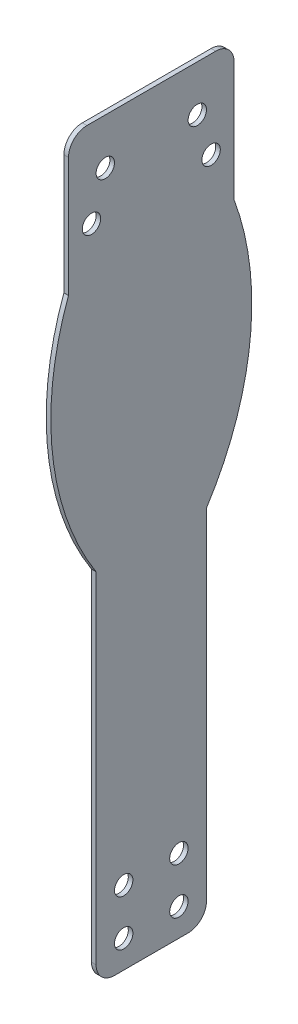
SolidWorks part; units mm, degrees
material "PVC 0.007 Plasticized"
ref_plane "Front Plane" through (0, 0, 0) normal (0, 0, 1) x (1, 0, 0)
ref_plane "Top Plane" through (0, 0, 0) normal (0, 1, 0) x (1, 0, 0)
ref_plane "Right Plane" through (0, 0, 0) normal (1, 0, 0) x (0, 0, -1)
sketch "Sketch1" plane through (0, 0, 0) normal (1, 0, 0) x (0, 0, -1)
  line L0 (12, -163) -> (12, -85)
  line L1 (-18, 0) -> (18, 0)
  line L2 (-18, 0) -> (-18, -163) construction
  line L3 (-18, -163) -> (18, -163) construction
  line L4 (18, 0) -> (18, -163) construction
  line L5 (-18, 0) -> (18, -163) construction
  line L6 (-18, -163) -> (18, 0) construction
  line L7 (-12, -163) -> (-12, -85)
  line L8 (12, -85) -> (-12, -85) construction
  line L9 (18, -30) -> (-18, -30) construction
  line L10 (18, 0) -> (18, -30)
  line L11 (-18, 0) -> (-18, -30)
  line L12 (-21.8408, -51.4826) -> (21.8408, -51.4826) construction
  line L13 (12, -163) -> (-12, -163)
  arc A0 (18, -30) -> (12, -85) centre (-40.1592, -51.4826) cw
  arc A1 (-18, -30) -> (-12, -85) centre (40.1592, -51.4826) ccw
  point P4 (0, -81.5)
  point P5 (0, 0)
  point P10 (0, -85)
  dimension "D6" = 62
  dimension "D7" = 62
  dimension "D1" = 30
  dimension "D2" = 36
  dimension "D3" = 24
  dimension "D4" = 163
  dimension "D5" = 55
  dimension "D8" = 43.6815
extrude "Boss-Extrude1" add sketch "Sketch1" along normal blind 1 contours L1 L10 A0 L0 L13 L7 A1 L11
hole_wizard "Ø4.0 (4) Diameter Hole3" positions "Sketch6" profile "Sketch7" hole size "Ø4.0" standard "ISO" end condition through all
sketch "Sketch6" plane through (0, 0, 0) normal (-1, 0, 0) x (0, 0, 1)
  point P0 (10, -10)
  point P3 (-10, -10)
sketch "Sketch7" plane through (0, -10, 10) normal (0, 1, 0) x (0, 0, 1)
  line L0 (0, 0) -> (0, 1)
  line L1 (0, 1) -> (2, 1)
  line L2 (2, 1) -> (2, 0)
  line L5 (2, 0) -> (0, 0)
  line L11 (0, -6.35) -> (0, 107.95) construction
  dimension "Thru Hole Dia." = 4
  dimension "Thru Hole Depth" = 1
hole_wizard "Ø4.0 (4) Diameter Hole2" positions "Sketch8" profile "Sketch9" hole size "Ø4.0" standard "ISO" end condition through all
sketch "Sketch8" plane through (0, 0, 0) normal (-1, 0, 0) x (0, 0, 1)
  point P4 (-13, -19)
  point P7 (13, -19)
sketch "Sketch9" plane through (0, -19, -13) normal (0, 1, 0) x (0, 0, 1)
  line L0 (0, 0) -> (0, 1)
  line L1 (0, 1) -> (2, 1)
  line L2 (2, 1) -> (2, 0)
  line L5 (2, 0) -> (0, 0)
  line L11 (0, -6.35) -> (0, 107.95) construction
  dimension "Thru Hole Dia." = 4
  dimension "Thru Hole Depth" = 1
hole_wizard "Ø4.0 (4) Diameter Hole1" positions "Sketch12" profile "Sketch11" hole size "Ø4.0" standard "ISO" end condition through all
sketch "Sketch12" plane through (1, 0, 0) normal (1, 0, 0) x (0, 0, -1)
  line L1 (12, -163) -> (-12, -163) construction
  point P0 (-6, -157)
  point P2 (6, -157)
  dimension "D1" = 12
  dimension "D2" = 6
  dimension "D3" = 6
sketch "Sketch11" plane through (1, -157, 6) normal (0, 1, 0) x (0, 0, -1)
  line L0 (0, 0) -> (0, 1)
  line L1 (0, 1) -> (2, 1)
  line L2 (2, 1) -> (2, 0)
  line L5 (2, 0) -> (0, 0)
  line L11 (0, -6.35) -> (0, 107.95) construction
  dimension "Thru Hole Dia." = 4
  dimension "Thru Hole Depth" = 1
pattern_linear "LPattern1" count 2 spacing 10 along (0, 1, 0) of "Ø4.0 (4) Diameter Hole1"
fillet "Fillet1" radius 4 4 edges at (0.5, -163, -12) (0.5, -163, 12) (0.5, 0, 18) (0.5, 0, -18)
